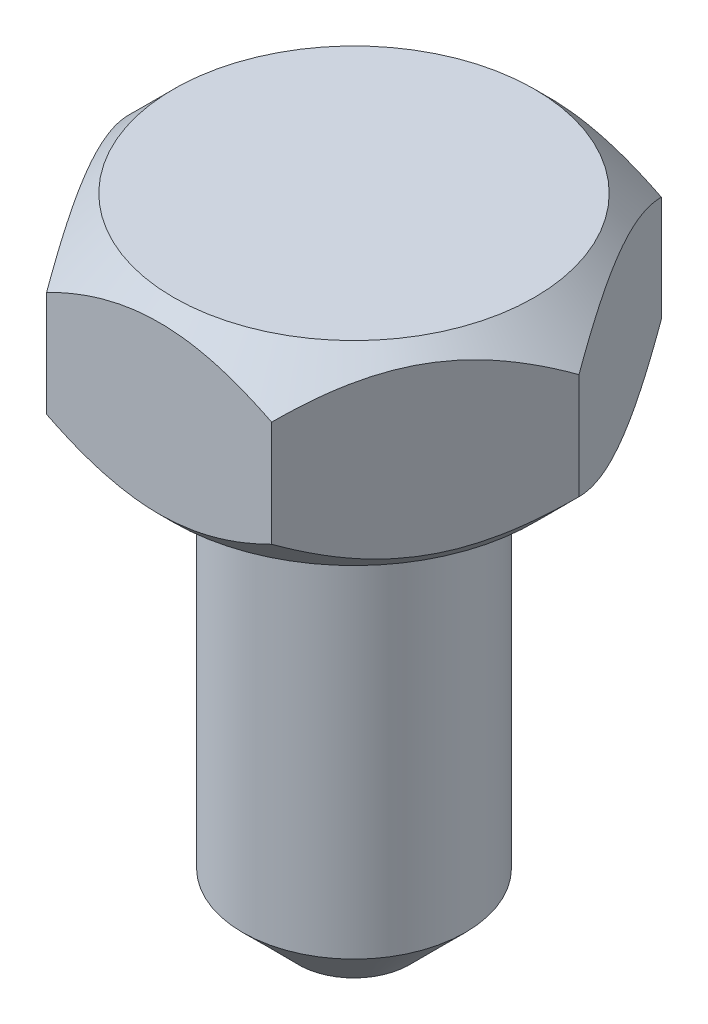
SolidWorks part; units mm, degrees
ref_plane "Спереди" through (0, 0, 0) normal (0, 0, 1) x (1, 0, 0)
ref_plane "Сверху" through (0, 0, 0) normal (0, 1, 0) x (1, 0, 0)
ref_plane "Справа" through (0, 0, 0) normal (1, 0, 0) x (0, 0, -1)
sketch "Эскиз1" plane through (0, 0, 0) normal (0, 1, 0) x (1, 0, 0)
  line L0 (-2.0207, 3.5) -> (2.0207, 3.5)
  line L1 (2.0207, 3.5) -> (4.0415, 0)
  line L2 (4.0415, 0) -> (2.0207, -3.5)
  line L3 (2.0207, -3.5) -> (-2.0207, -3.5)
  line L4 (-2.0207, -3.5) -> (-4.0415, 0)
  line L5 (-4.0415, 0) -> (-2.0207, 3.5)
  dimension "D5" = 3.5
  dimension "D2" = 120
  dimension "D3" = 120
  dimension "D4" = 120
  dimension "D6" = 3.5
  dimension "D7" = 3.5
  dimension "D8" = 3.5
  dimension "D9" = 3.5
  dimension "D10" = 120
  dimension "D11" = 3.5
extrude "Вытянуть1" add sketch "Эскиз1" against normal blind 3.5
sketch "Эскиз5" plane through (0, -3.5, 0) normal (0, -1, 0) x (1, 0, 0)
  circle A0 centre (0, 0) radius 2
  dimension "D1" = 4
extrude "Вытянуть2" add sketch "Эскиз5" along normal blind 8
chamfer "Фаска1" distance 1 angle 45 1 edges at (0, -11.5, -2)
ref_axis "Ось1" through (0, -3.5, 0) along (0, -1, 0)
ref_plane "Плоскость1" through (0, 0, 0) normal (0, 0, 1) x (1, 0, 0)
sketch "Эскиз4" plane through (0, 0, 0) normal (0, 0, 1) x (1, 0, 0)
  line L0 (-4.0415, -0.8) -> (-3.2415, 0)
  line L1 (-4.0415, -3.5) -> (-4.0415, 0) construction
  line L2 (-4.0415, 0) -> (-2.0207, 0) construction
  line L3 (-3.2415, 0) -> (-4.0415, 0)
  line L4 (-4.0415, 0) -> (-4.0415, -0.8)
  line L5 (-4.0415, -2.7) -> (-3.2415, -3.5)
  line L6 (-4.0415, -3.5) -> (-2.0207, -3.5) construction
  line L7 (-3.2415, -3.5) -> (-4.0415, -3.5)
  line L8 (-4.0415, -3.5) -> (-4.0415, -2.7)
  dimension "D1" = 0.8
  dimension "D2" = 0.8
  dimension "D3" = 0.8
  dimension "D4" = 0.8
revolve "Вырез-Повернуть1" cut sketch "Эскиз4" angle 360 about axis through (0, -3.5, 0) along (0, -1, 0)
